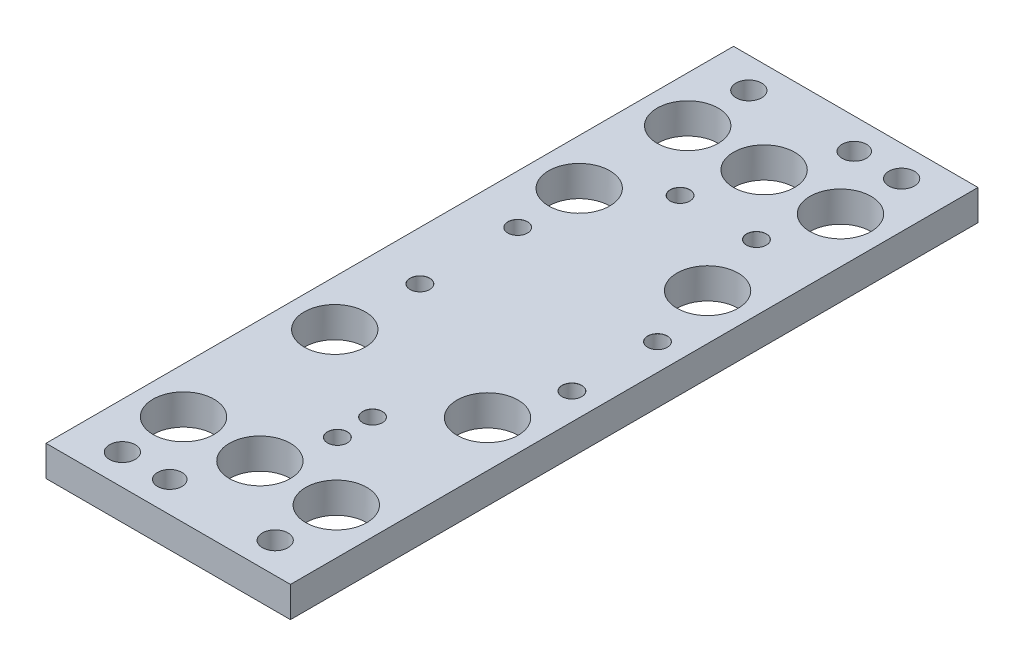
SolidWorks part; units mm, degrees
material "K110"
ref_plane "Front Plane" through (0, 0, 0) normal (0, 0, 1) x (1, 0, 0)
ref_plane "Top Plane" through (0, 0, 0) normal (0, 1, 0) x (1, 0, 0)
ref_plane "Right Plane" through (0, 0, 0) normal (1, 0, 0) x (0, 0, -1)
sketch "Sketch1" plane through (0, 0, 0) normal (0, 1, 0) x (1, 0, 0)
  line L1 (-40, -112.5) -> (40, -112.5)
  line L2 (-40, -112.5) -> (-40, 112.5)
  line L3 (-40, 112.5) -> (40, 112.5)
  line L4 (40, -112.5) -> (40, 112.5)
  line L5 (-40, -112.5) -> (40, 112.5) construction
  line L6 (-40, 112.5) -> (40, -112.5) construction
  point P0 (0, 0)
  dimension "D1" = 225
  dimension "D2" = 80
extrude "Boss-Extrude1" add sketch "Sketch1" against normal blind 10
sketch "Sketch2" plane through (0, 0, 0) normal (0, 1, 0) x (1, 0, 0)
  circle A0 centre (25, -82.5) radius 10 construction
  circle A1 centre (0, -82.5) radius 10 construction
  circle A2 centre (-25, -82.5) radius 10 construction
  circle A3 centre (25, -33) radius 10 construction
  circle A4 centre (-25, -33) radius 10 construction
  circle A6 centre (25, 39) radius 10 construction
  circle A7 centre (-25, 47) radius 10 construction
  circle A8 centre (-25, 82.5) radius 10 construction
  circle A9 centre (0, 82.5) radius 10 construction
  circle A10 centre (25, 82.5) radius 10 construction
  circle A11 centre (25, -82.5) radius 10
  circle A12 centre (0, -82.5) radius 10
  circle A13 centre (-25, -82.5) radius 10
  circle A14 centre (25, -33) radius 10
  circle A15 centre (-25, -33) radius 10
  circle A17 centre (25, 39) radius 10
  circle A18 centre (-25, 47) radius 10
  circle A19 centre (-25, 82.5) radius 10
  circle A20 centre (0, 82.5) radius 10
  circle A21 centre (25, 82.5) radius 10
extrude "Cut-Extrude1" cut sketch "Sketch2" against normal up to next
hole_wizard "M8 Clearance Hole1" positions "Sketch9" profile "Sketch8" hole size "M8" standard "ISO" end condition through all
sketch "Sketch9" plane through (0, 0, 0) normal (0, 1, 0) x (1, 0, 0)
  point P0 (25, -102.5)
  point P3 (-25, -102.5)
  point P6 (25, 102.5)
  point P9 (-25, 102.5)
sketch "Sketch8" plane through (25, 0, 102.5) normal (1, 0, 0) x (0, 0, 1)
  line L0 (0, 0) -> (0, 10)
  line L1 (0, 10) -> (4.2, 10)
  line L2 (4.2, 10) -> (4.2, 0)
  line L5 (4.2, 0) -> (0, 0)
  line L11 (0, -6.35) -> (0, 107.95) construction
  dimension "Thru Hole Dia." = 8.4
  dimension "Thru Hole Depth" = 10
hole_wizard "Ø8.0mm Dowel Hole1" positions "Sketch12" profile "Sketch11" hole size "Ø8.0" standard "ISO" end condition through all
sketch "Sketch12" plane through (0, 0, 0) normal (0, 1, 0) x (1, 0, 0)
  point P0 (-9.5, -102.5)
  point P3 (9.5, 102.5)
sketch "Sketch11" plane through (-9.5, 0, 102.5) normal (1, 0, 0) x (0, 0, 1)
  line L0 (0, 0) -> (0, 10)
  line L1 (0, 10) -> (4, 10)
  line L2 (4, 10) -> (4, 0)
  line L5 (4, 0) -> (0, 0)
  line L11 (0, -6.35) -> (0, 107.95) construction
  dimension "Thru Hole Dia." = 8
  dimension "Thru Hole Depth" = 10
hole_wizard "M6 Clearance Hole1" positions "Sketch15" profile "Sketch14" hole size "M6" standard "ISO" end condition through all
sketch "Sketch15" plane through (0, 0, 0) normal (0, 1, 0) x (1, 0, 0)
  point P0 (-24, -6.14)
  point P3 (-24, 25.86)
  point P6 (31.25, -11.64)
  point P9 (31.25, 16.36)
  point P12 (18.5, 61.5)
  point P15 (-6.5, 61.5)
  point P18 (6, -51.64)
  point P27 (6, -63.14)
sketch "Sketch14" plane through (-24, 0, 6.14) normal (1, 0, 0) x (0, 0, 1)
  line L0 (0, 0) -> (0, 10)
  line L1 (0, 10) -> (3.2, 10)
  line L2 (3.2, 10) -> (3.2, 0.025)
  line L3 (3.2, 0.025) -> (3.225, 0)
  line L5 (3.225, 0) -> (0, 0)
  line L6 (-3.2, 0.025) -> (-3.225, 0) construction
  line L11 (0, -6.35) -> (0, 107.95) construction
  dimension "Thru Hole Dia." = 6.4
  dimension "Thru Hole Depth" = 10
  dimension "Near C'Sink Dia." = 6.45
  dimension "Near C'Sink Angle" = 90
